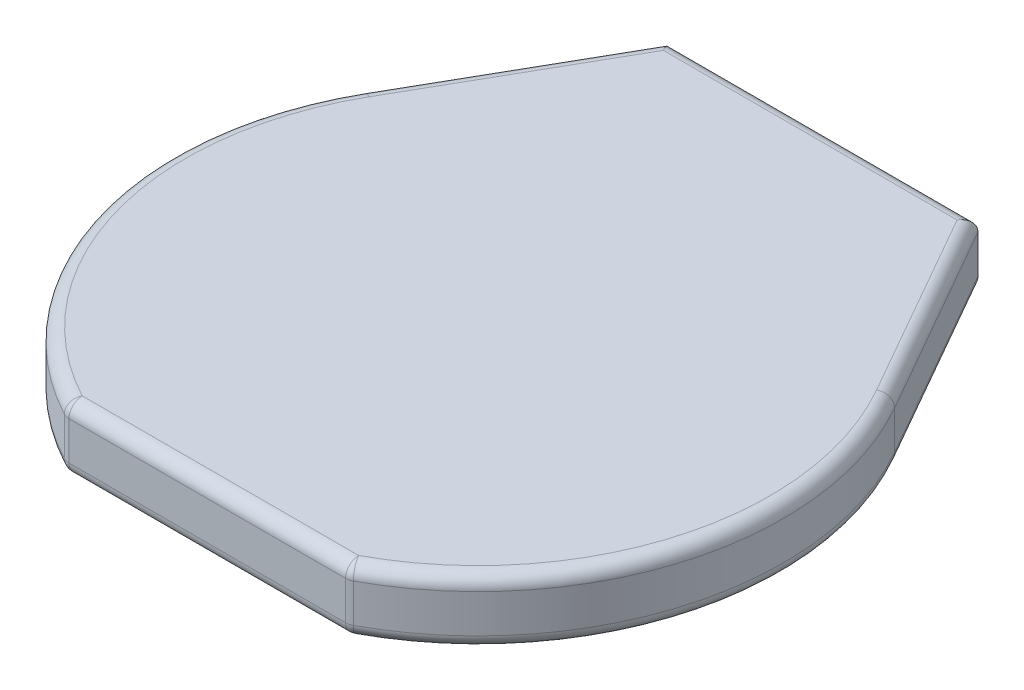
SolidWorks part; units mm, degrees
ref_plane "Front Plane" through (0, 0, 0) normal (0, 0, 1) x (1, 0, 0)
ref_plane "Top Plane" through (0, 0, 0) normal (0, 1, 0) x (1, 0, 0)
ref_plane "Right Plane" through (0, 0, 0) normal (1, 0, 0) x (0, 0, -1)
sketch "Sketch1" plane through (0, 0, 0) normal (0, 1, 0) x (1, 0, 0)
  line L0 (-8.04, -15.3747) -> (8.04, -15.3747)
  line L1 (0, -55) -> (0, 55) construction
  line L2 (-8.78, 19.6253) -> (8.78, 19.6253)
  line L3 (-8.78, 19.6253) -> (-15.0708, 8.5961)
  line L4 (8.78, 19.6253) -> (15.0708, 8.5961)
  arc A0 (-15.0708, 8.5961) -> (-8.04, -15.3747) centre (0, 0) ccw
  arc A1 (8.04, -15.3747) -> (15.0708, 8.5961) centre (0, 0) ccw
  point P5 (0, -15.3747)
  point P11 (0, 19.6253)
  dimension "D1" = 34.7
  dimension "D2" = 16.08
  dimension "D3" = 17.56
  dimension "D4" = 35
extrude "Boss-Extrude1" add sketch "Sketch1" along normal blind 3.68
fillet "Fillet1" radius 0.75 14 edges at (-11.9254, 0, -14.1107) (16.6486, 0, 4.8832) (-11.9254, 3.68, -14.1107) (11.9254, 3.68, -14.1107) (-8.04, 1.84, 15.3747) (8.04, 1.84, 15.3747) (0, 0, -19.6253) (-16.6486, 0, 4.8832) (0, 0, 15.3747) (11.9254, 0, -14.1107) (0, 3.68, -19.6253) (-16.6486, 3.68, 4.8832) (0, 3.68, 15.3747) (16.6486, 3.68, 4.8832)
